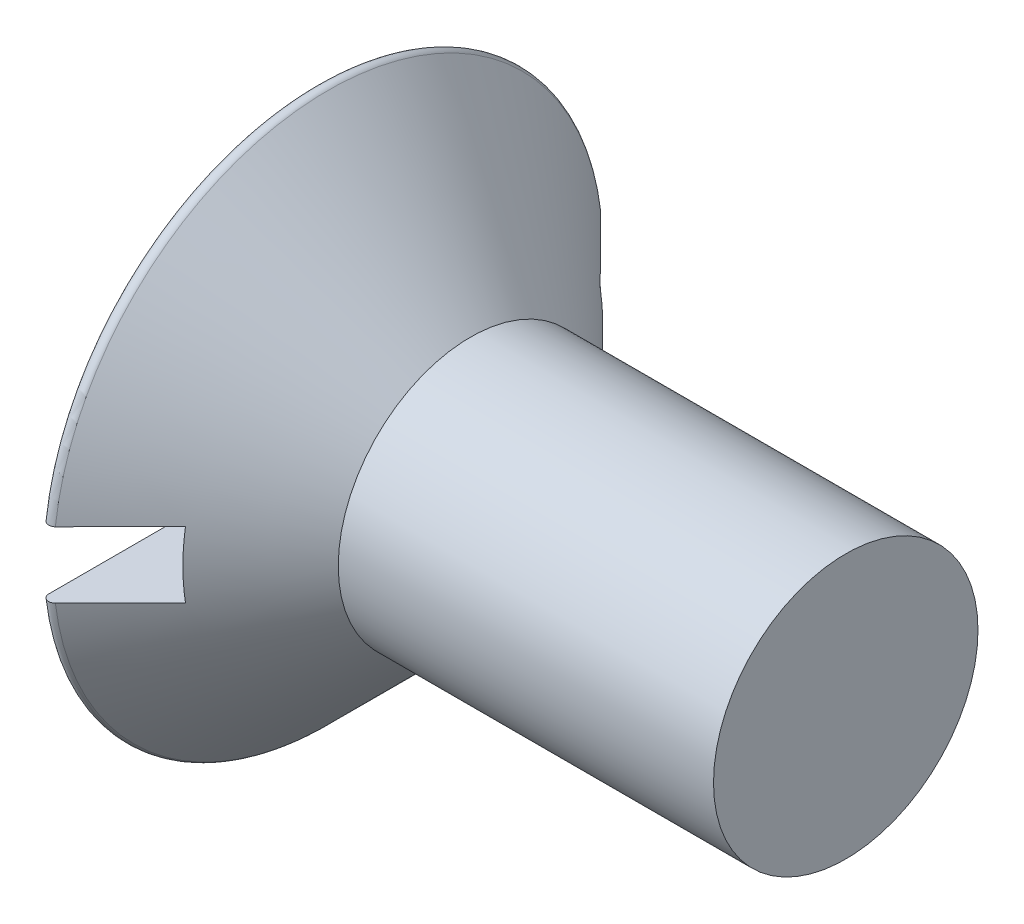
SolidWorks part; units mm, degrees
ref_plane "Front" through (0, 0, 0) normal (0, 0, 1) x (1, 0, 0)
ref_plane "Top" through (0, 0, 0) normal (0, 1, 0) x (1, 0, 0)
ref_plane "Right" through (0, 0, 0) normal (1, 0, 0) x (0, 0, -1)
other "Configuration Table"
sketch "Sketch1" plane through (0, 0, 0) normal (0, 0, 1) x (1, 0, 0)
  line L0 (0, 0) -> (0, 8.65)
  line L1 (0, 8.65) -> (4.65, 4)
  line L3 (16, 4) -> (16, 0)
  line L4 (16, 0) -> (0, 0)
  line L5 (-5.5696, 0) -> (0, 0) construction
  line L6 (4.65, 4) -> (16, 4)
  dimension "l" = 16
  dimension "dk" = 17.3
  dimension "k" = 4.65
  dimension "d" = 8
revolve "Base" add sketch "Sketch1" angle 360 about L5
cosmetic thread "ThreadCosmetic1" [suppressed] parameters "D1"=11.35, "D2"=6.647
fillet "HeadFillet" radius 0.2 1 edges at (0, 0, 8.65)
sketch "Sketch2" plane through (0, 0, 0) normal (0, 0, 1) x (1, 0, 0)
  line L1 (0, 1) -> (2.3, 1)
  line L2 (0, 1) -> (0, -1)
  line L3 (0, -1) -> (2.3, -1)
  line L4 (2.3, 1) -> (2.3, -1)
  dimension "t" = 2.3
  dimension "n" = 2
  dimension "m" = 1
extrude "Notch" cut sketch "Sketch2" against normal through all and the other way through all
sketch "Sketch3" plane through (0, 0, 0) normal (0, 0, 1) x (1, 0, 0)
  line L0 (4.4877, 0) -> (-0.464, 0) construction
  line L1 (4.65, 9.19) -> (-22, 9.19)
  line L2 (4.65, 9.19) -> (4.65, 4.19)
  line L3 (4.65, 4.19) -> (-25.2, 4.19)
  line L4 (-22, 9.19) -> (-22, 4)
  line L6 (-22, 4) -> (-25.2, 4.19)
  line L7 (16, -4) -> (16, 4) construction
  line L10 (0, 8.1672) -> (0, 1) construction
  dimension "b" = 38
  dimension "x" = 3.2
  dimension "D4" = 5
  dimension "k" = 4.65
  dimension "d" = 8
  dimension "d1" = 8.38
sketch "Sketch4" plane through (0, 0, 0) normal (0, 0, 1) x (1, 0, 0)
  line L0 (16, 3.4141) -> (16.3382, 4)
  line L1 (16.3382, 4) -> (16.3382, 4.6765)
  line L2 (16.3382, 4.6765) -> (15.6618, 4.6765)
  line L3 (15.6618, 4.6765) -> (15.6618, 4)
  line L4 (15.6618, 4) -> (16, 3.4141)
  line L5 (16, -4) -> (16, 4) construction
  line L6 (0, 0) -> (84.1591, 0) construction
  dimension "D1" = 8
  dimension "D2" = 0.6765
revolve "Cut-Revolve10" [suppressed] cut sketch "Sketch4" angle 360 about L6
pattern_linear "LPattern10" [suppressed] count 14 spacing 0.8118 along (1, 0, 0)
equation "\"m@Sketch2\" = \"n@Sketch2\" / 2"
equation "\"D1@Sketch4\" = \"d@Sketch1\""
equation "\"D2@Sketch4\" =  ( \"d@Sketch1\" - \"D2@ThreadCosmetic1\" )  / 2"
equation "\"D3@LPattern10\" = \"D2@Sketch4\" * 1.2"
equation "\"D1@LPattern10\" = \"D1@ThreadCosmetic1\" / \"D3@LPattern10\""
